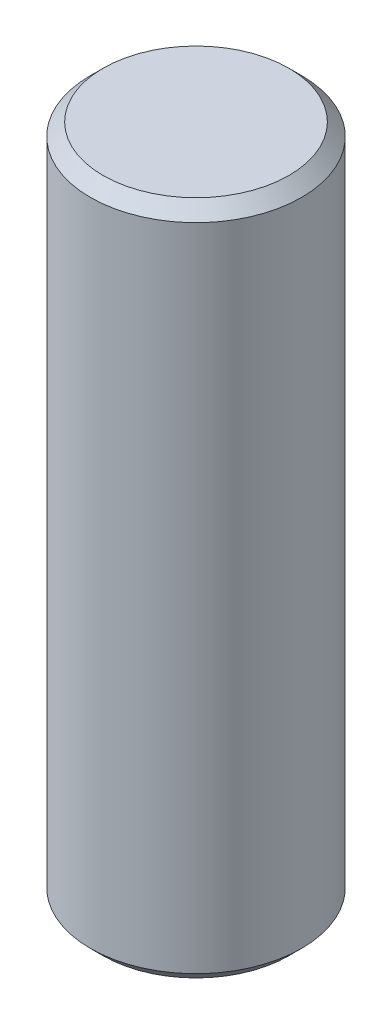
SolidWorks part; units mm, degrees
ref_plane "Front Plane" through (0, 0, 0) normal (0, 0, 1) x (1, 0, 0)
ref_plane "Top Plane" through (0, 0, 0) normal (0, 1, 0) x (1, 0, 0)
ref_plane "Right Plane" through (0, 0, 0) normal (1, 0, 0) x (0, 0, -1)
sketch "Sketch1" plane through (0, 0, 0) normal (0, 1, 0) x (1, 0, 0)
  circle A0 centre (0, 0) radius 2.5
  dimension "D1" = 5
extrude "Boss-Extrude1" add sketch "Sketch1" along normal blind 16
chamfer "Chamfer1" distance 0.3 angle 45 2 edges at (0, 0, 2.5) (0, 16, 2.5)
